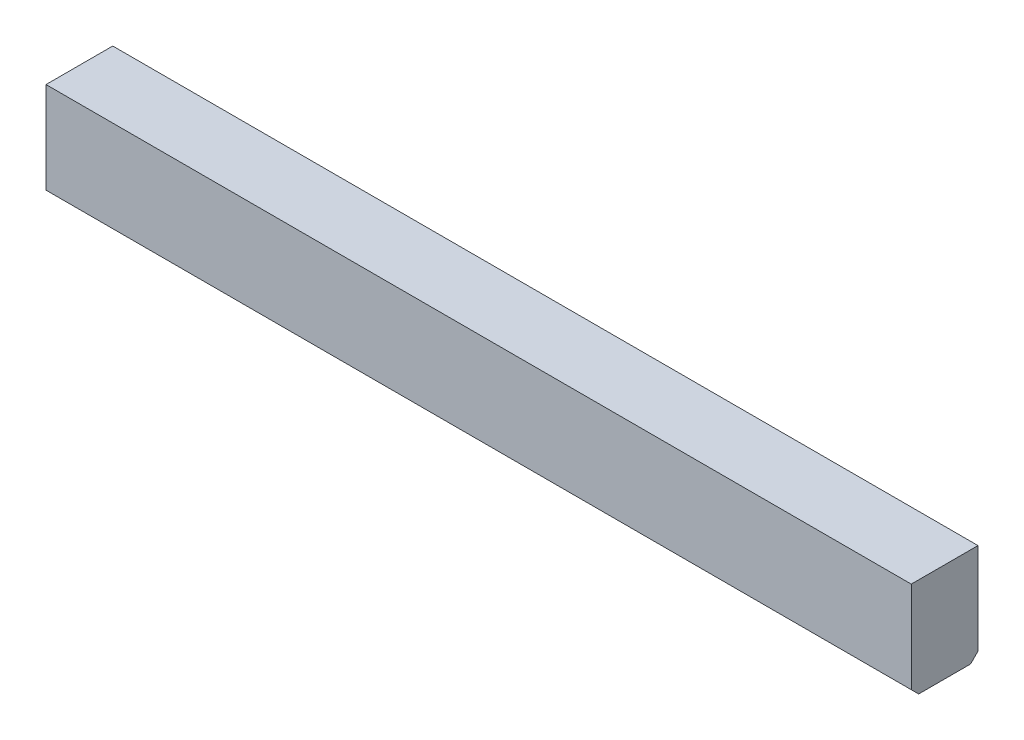
SolidWorks part; units mm, degrees
ref_plane "Plan de face" through (0, 0, 0) normal (0, 0, 1) x (1, 0, 0)
ref_plane "Plan de dessus" through (0, 0, 0) normal (0, 1, 0) x (1, 0, 0)
ref_plane "Plan de droite" through (0, 0, 0) normal (1, 0, 0) x (0, 0, -1)
sketch "Esquisse1" plane through (0, 0, 0) normal (0, 0, 1) x (1, 0, 0)
  line L1 (0, 0) -> (350, 0)
  line L2 (0, 0) -> (0, 40)
  line L3 (0, 40) -> (350, 40)
  line L4 (350, 0) -> (350, 40)
  dimension "D1" = 40
  dimension "D2" = 350
extrude "Boss.-Extru.1" add sketch "Esquisse1" along normal blind 27
chamfer "Chanfrein1" distance 3 angle 45 2 edges at (175, 0, 0) (175, 0, 27)
